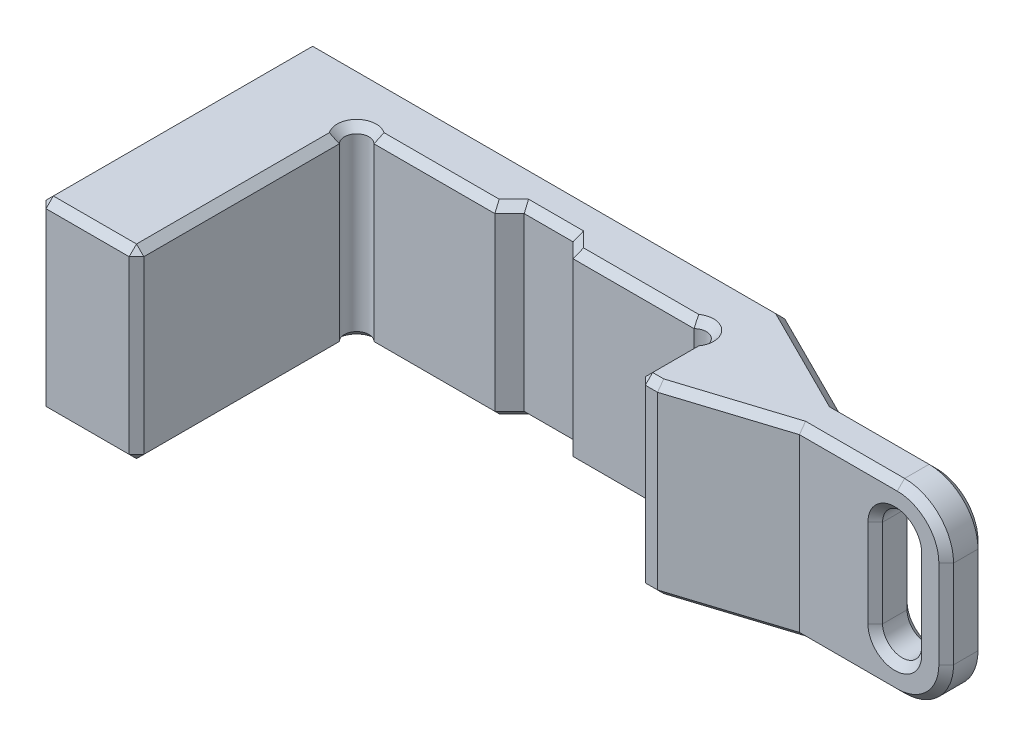
SolidWorks part; units mm, degrees
material "PET"
ref_plane "Front Plane" through (0, 0, 0) normal (0, 0, 1) x (1, 0, 0)
ref_plane "Top Plane" through (0, 0, 0) normal (0, 1, 0) x (1, 0, 0)
ref_plane "Right Plane" through (0, 0, 0) normal (1, 0, 0) x (0, 0, -1)
sketch "Sketch1" plane through (0, 0, 0) normal (0, 1, 0) x (1, 0, 0)
  line L0 (0, 0) -> (0, 56)
  line L1 (0, 56) -> (96.5, 56)
  line L2 (96.5, 56) -> (118.5, 45)
  line L3 (118.5, 45) -> (148.5, 45)
  line L4 (148.5, 45) -> (148.5, 37)
  line L5 (148.5, 37) -> (118.5, 37)
  line L11 (20, 41.4645) -> (20, 0)
  line L12 (20, 0) -> (0, 0)
  line L13 (118.5, 37) -> (96.5, 30)
  line L14 (96.5, 30) -> (92.5, 30)
  line L15 (92.5, 30) -> (92.5, 41.4645)
  line L17 (23.5355, 45) -> (48.25, 45)
  line L18 (48.25, 45) -> (51.25, 48)
  line L19 (51.25, 48) -> (61.25, 48)
  line L20 (61.25, 48) -> (64.25, 45)
  line L21 (64.25, 45) -> (88.9645, 45)
  line L22 (20, 41.4645) -> (23.5355, 45) construction
  line L23 (88.9645, 45) -> (92.5, 41.4645) construction
  arc A0 (20, 41.4645) -> (23.5355, 45) centre (21.7678, 43.2322) cw
  arc A1 (88.9645, 45) -> (92.5, 41.4645) centre (90.7322, 43.2322) cw
  dimension "D14" = 2.5
  dimension "D15" = 2.5
  dimension "D2" = 20
  dimension "D3" = 72.5
  dimension "D4" = 10
  dimension "D5" = 3
  dimension "D6" = 11
  dimension "D7" = 4
  dimension "D8" = 26
  dimension "D9" = 30
  dimension "D10" = 45
  dimension "D11" = 8
  dimension "D12" = 135
  dimension "D13" = 135
  dimension "D16" = 15
extrude "Create profile" add sketch "Sketch1" along normal blind 38
sketch "Sketch3" plane through (0, 0, -45) normal (0, 0, -1) x (-1, 0, 0)
  line L0 (-138, 28) -> (-138, 10) construction
  line L1 (-134, 28) -> (-134, 10)
  line L2 (-142, 28) -> (-142, 10)
  line L3 (-148.5, 38) -> (-148.5, 0) construction
  arc A0 (-134, 28) -> (-142, 28) centre (-138, 28) ccw
  arc A1 (-142, 10) -> (-134, 10) centre (-138, 10) ccw
  point P2 (-138, 19)
  point P7 (0, 0)
  point P10 (-148.5, 19)
  point P11 (0, 0)
  dimension "D1" = 8
  dimension "16" = 18
  dimension "D2" = 6.5
extrude "Cut shackle hole" cut sketch "Sketch3" against normal through all
fillet "Round Edges" radius 10 2 edges at (148.5, 0, -41) (148.5, 38, -41)
chamfer "Unecessary chamfers" distance 1.5 angle 45 52 edges at (148.5, 19, -37) (148.5, 19, -45) (145.5711, 2.9289, -45) (145.5711, 2.9289, -37) (145.5711, 35.0711, -37) (145.5711, 35.0711, -45) (128.5, 0, -45) (107.5, 0, -50.5) (48.25, 0, -56) (0, 0, -28) (10, 0, 0) (20, 0, -20.7322) (20, 0, -45) (35.8928, 0, -45) (49.75, 0, -46.5) (56.25, 0, -48) (62.75, 0, -46.5) (76.6072, 0, -45) (92.5, 0, -45) (92.5, 0, -35.7322) (128.5, 0, -37) (107.5, 0, -33.5) (94.5, 0, -30) (128.5, 38, -37) (107.5, 38, -33.5) (94.5, 38, -30) (92.5, 19, -30) (92.5, 38, -35.7322) (92.5, 38, -45) (76.6072, 38, -45) (62.75, 38, -46.5) (56.25, 38, -48) (49.75, 38, -46.5) (35.8928, 38, -45) (20, 38, -45) (20, 38, -20.7322) (20, 19, 0) (10, 38, 0) (0, 19, 0) (0, 38, -28) (128.5, 38, -45) (107.5, 38, -50.5) (48.25, 38, -56) (0, 19, -56) (138, 32, -45) (142, 19, -45) (134, 19, -45) (138, 6, -45) (142, 19, -37) (138, 6, -37) (138, 32, -37) (134, 19, -37)
